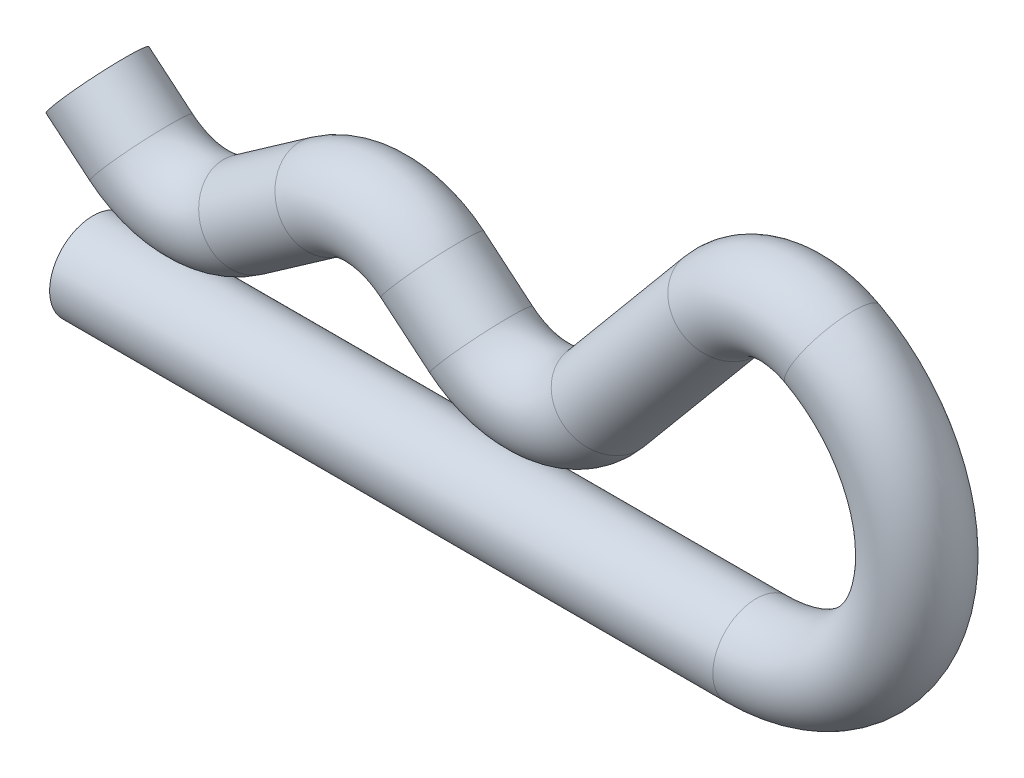
SolidWorks part; units mm, degrees
material "Chrome Stainless Steel"
ref_plane "Front Plane" through (0, 0, 0) normal (0, 0, 1) x (1, 0, 0)
ref_plane "Top Plane" through (0, 0, 0) normal (0, 1, 0) x (1, 0, 0)
ref_plane "Right Plane" through (0, 0, 0) normal (1, 0, 0) x (0, 0, -1)
sketch "Sketch1" plane through (0, 0, 0) normal (0, 0, 1) x (1, 0, 0)
  line L0 (0, 0) -> (75, 0)
  line L1 (71.1898, 31.7791) -> (58.0008, 15.9797)
  line L2 (43.9156, 14.7114) -> (38.3765, 19.3353)
  line L3 (26.2324, 19.8502) -> (17.6038, 13.8084)
  line L4 (5.4597, 14.3233) -> (0.509, 18.456)
  arc A0 (75, 0) -> (83.5983, 34.1804) centre (75, 18.1717) ccw
  arc A1 (17.6038, 13.8084) -> (5.4597, 14.3233) centre (11.8681, 22) cw
  arc A2 (71.1898, 31.7791) -> (83.5983, 34.1804) centre (78.8666, 25.3707) cw
  arc A3 (43.9156, 14.7114) -> (58.0008, 15.9797) centre (50.324, 22.3881) ccw
  arc A4 (38.3765, 19.3353) -> (26.2324, 19.8502) centre (31.9681, 11.6586) ccw
  dimension "D1" = 10
  dimension "D3" = 22
  dimension "D2" = 75
sketch "Sketch2" plane through (0, 0, 0) normal (1, 0, 0) x (0, 0, -1)
  circle A0 centre (0, 0) radius 4.9
  dimension "D1" = 9.8
sweep "Sweep1" add profiles "Sketch2" path "Sketch1"
